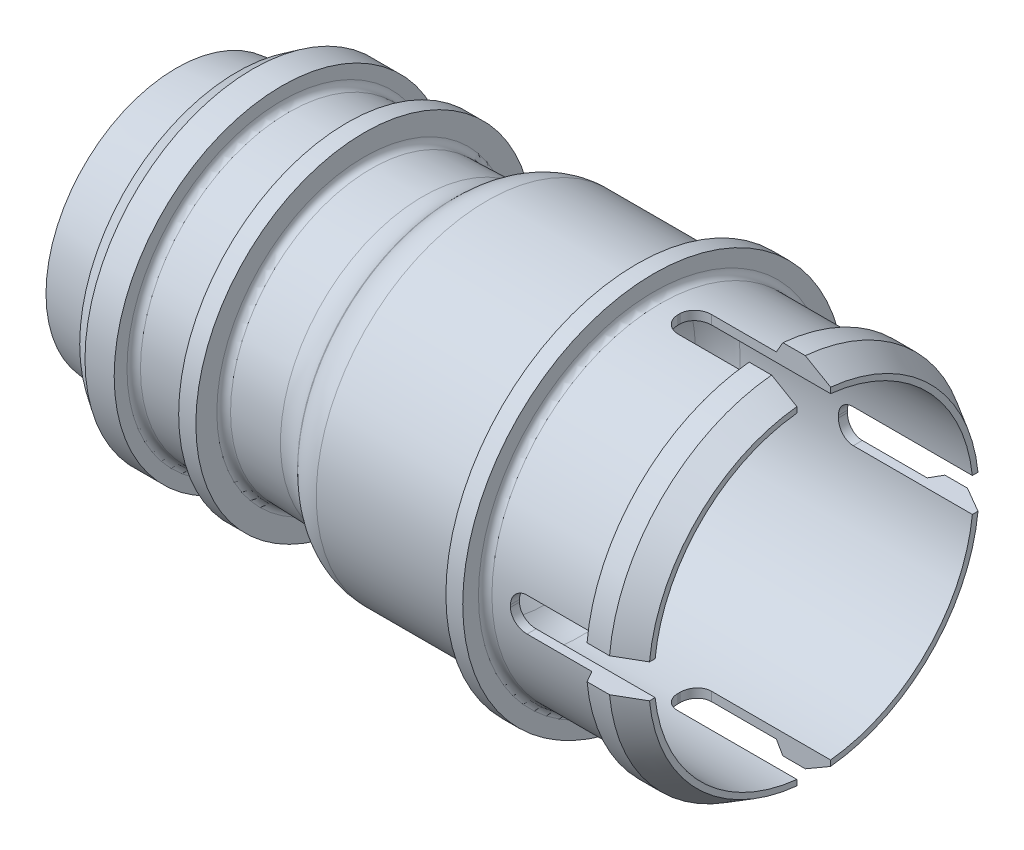
SolidWorks part; units mm, degrees
ref_plane "Front Plane" through (0, 0, 0) normal (0, 0, 1) x (1, 0, 0)
ref_plane "Top Plane" through (0, 0, 0) normal (0, 1, 0) x (1, 0, 0)
ref_plane "Right Plane" through (0, 0, 0) normal (1, 0, 0) x (0, 0, -1)
sketch "Sketch1" plane through (0, 0, 0) normal (0, 0, 1) x (1, 0, 0)
  line L0 (-11.7761, 0) -> (32.5958, 0) construction
  line L1 (-39.37, 13.7795) -> (0, 13.7795)
  line L2 (0, 13.7795) -> (0, 18.034) construction
  line L8 (-39.37, 14.732) -> (-39.37, 13.7795)
  line L12 (-39.37, 14.732) -> (-32.512, 15.621)
  line L13 (-32.512, 15.621) -> (-32.512, 17.78)
  line L14 (-32.512, 17.78) -> (-30.734, 18.9611)
  line L15 (-30.734, 18.9611) -> (-27.432, 18.9611)
  line L16 (-27.432, 18.9611) -> (-27.432, 16.7513)
  line L17 (-27.432, 16.7513) -> (-20.066, 16.7513)
  line L18 (-20.066, 16.7513) -> (-20.066, 19.0373)
  line L19 (-20.066, 19.0373) -> (-18.1229, 19.0373)
  line L20 (-18.1229, 19.0373) -> (-18.1229, 15.875)
  line L21 (-18.1229, 15.875) -> (-9.4999, 16.1541)
  line L22 (-6.35, 19.304) -> (-6.35, 16.256) construction
  line L23 (-20.828, 19.7993) -> (-18.1229, 19.7993) construction
  line L34 (-39.37, 15.5004) -> (-33.274, 16.2906) construction
  line L35 (-33.274, 16.2906) -> (-33.274, 18.1886) construction
  line L36 (-33.274, 18.1886) -> (-30.964, 19.7231) construction
  line L37 (-30.964, 19.7231) -> (-26.67, 19.7231) construction
  line L38 (-26.67, 19.7231) -> (-26.67, 17.5133) construction
  line L39 (-26.67, 17.5133) -> (-20.828, 17.5133) construction
  line L40 (-20.828, 17.5133) -> (-20.828, 19.7993) construction
  line L41 (-18.1229, 19.0373) -> (-18.1229, 19.7993) construction
  line L42 (-20.828, 19.7993) -> (-17.3609, 19.7993) construction
  line L43 (-17.3609, 19.7993) -> (-17.3609, 16.6621) construction
  line L44 (-17.3609, 16.6621) -> (-7.112, 16.9937) construction
  line L45 (-7.112, 20.0814) -> (-7.112, 16.9937) construction
  line L46 (-7.112, 20.0814) -> (25.4456, 19.431) construction
  line L47 (25.4456, 19.431) -> (32.512, 18.583) construction
  line L48 (32.512, 18.583) -> (32.512, 16.0195) construction
  line L49 (0.762, 17.2421) -> (32.512, 16.0195) construction
  line L50 (0.762, 13.0175) -> (0.762, 17.2421) construction
  line L51 (-40.132, 13.0175) -> (0.762, 13.0175) construction
  line L52 (-40.132, 15.4016) -> (-40.132, 13.0175) construction
  line L54 (-40.132, 15.4016) -> (-33.274, 16.2906) construction
  line L55 (-20.828, 19.7993) -> (-23.114, 17.5133) construction
  line L56 (-33.274, 18.1886) -> (-35.4547, 16.0079) construction
  line L57 (-23.114, 17.5133) -> (-26.67, 17.5133) construction
  line L58 (-35.4547, 16.0079) -> (-39.37, 15.5004) construction
  line L59 (25.3924, 18.6699) -> (31.75, 17.907) construction
  line L60 (31.75, 17.907) -> (31.75, 16.8114) construction
  line L61 (0, 18.034) -> (31.75, 16.8114) construction
  line L62 (-6.35, 19.304) -> (25.3924, 18.6699) construction
  line L63 (4.2545, 18.034) -> (32.7046, 18.034)
  line L64 (32.7046, 18.034) -> (32.7046, 18.669)
  line L65 (32.7046, 18.669) -> (29.845, 20.32)
  line L66 (29.845, 20.32) -> (27.305, 20.32)
  line L68 (26.5718, 19.05) -> (14.605, 19.05)
  line L69 (14.605, 19.05) -> (14.605, 21.59)
  line L70 (14.605, 21.59) -> (12.7, 21.59)
  line L71 (12.7, 21.59) -> (12.7, 19.304)
  line L72 (12.7, 19.304) -> (-6.35, 19.304)
  line L73 (27.305, 20.32) -> (26.5718, 19.05)
  line L74 (-6.35, 19.304) -> (-9.4999, 16.1541)
  line L75 (-18.1229, 15.875) -> (-6.35, 16.256) construction
  line L76 (-9.4999, 16.1541) -> (-6.35, 16.256) construction
  line L77 (0, 13.7795) -> (4.2545, 18.034)
  line L78 (4.2545, 18.034) -> (0, 18.034) construction
  dimension "D3" = 38.1
  dimension "D4" = 120
  dimension "D5" = 27.559
  dimension "D6" = 29.464
  dimension "D7" = 6.858
  dimension "D8" = 30
  dimension "D9" = 2.54
  dimension "D10" = 7.366
  dimension "D11" = 1.9431
  dimension "D12" = 31.242
  dimension "D13" = 18.9611
  dimension "D14" = 5.08
  dimension "D15" = 16.7513
  dimension "D16" = 31.75
  dimension "D17" = 32.512
  dimension "D18" = 35.56
  dimension "D19" = 3.302
  dimension "D20" = 33.02
  dimension "D21" = 19.0373
  dimension "D23" = 45
  dimension "D24" = 45
  dimension "D25" = 1.905
  dimension "D26" = 1.016
  dimension "D27" = 2.54
  dimension "D28" = 12.7
  dimension "D29" = 0.635
  dimension "D30" = 12.7
  dimension "D31" = 6.35
  dimension "D32" = 1.27
  dimension "D33" = 1.27
  dimension "D34" = 45
  dimension "D35" = 45
  dimension "D22" = 0.762
revolve "Revolve1" add sketch "Sketch1" angle 360 about L0
ref_plane "Plane1" through (0, 21.336, 0) normal (0, 1, 0) x (1, 0, 0)
fillet "Fillet1" radius 0.762 5 edges at (-18.1229, 0, 15.875) (-20.066, 0, 16.7513) (-27.432, 0, 16.7513) (14.605, 0, 19.05) (12.7, 0, 19.304)
sketch "Sketch2" plane through (0, 0, 0) normal (0, 1, 0) x (1, 0, 0)
  line L0 (32.7046, -18.669) -> (32.7046, 18.669) construction
  line L1 (32.7046, -1.905) -> (17.4646, -1.905)
  line L2 (32.7046, -1.905) -> (32.7046, 1.905)
  line L3 (32.7046, 1.905) -> (17.4646, 1.905)
  line L4 (17.4646, -1.905) -> (17.4646, 1.905)
  line L5 (-55, 0) -> (55, 0) construction
  point P6 (32.7046, 0)
  dimension "D1" = 15.24
  dimension "D2" = 3.81
extrude "Cut-Extrude1" cut sketch "Sketch2" against normal through all both and the other way through all
fillet "Fillet4" radius 1.778 4 edges at (17.4646, 18.4438, 1.905) (17.4646, -18.4438, 1.905) (17.4646, -18.4438, -1.905) (17.4646, 18.4438, -1.905)
pattern_circular "CirPattern1" count 2 over 90 about axis through (14.605, 0, 0) along (-1, 0, 0) of "Cut-Extrude1", "Fillet4"
fillet "Fillet6" radius 5.08 4 edges at (-9.4999, 0, 16.1541) (-6.35, 0, 19.304) (0, 0, 13.7795) (4.2545, 0, 18.034)
